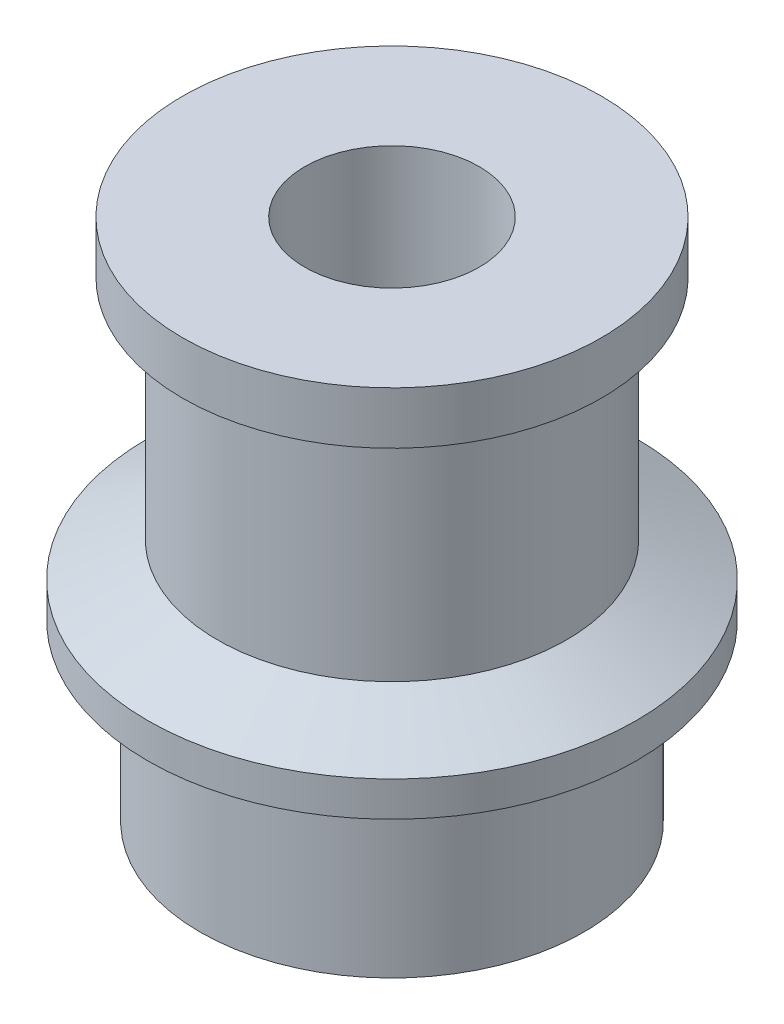
SolidWorks part; units mm, degrees
ref_plane "Front Plane" through (0, 0, 0) normal (0, 0, 1) x (1, 0, 0)
ref_plane "Top Plane" through (0, 0, 0) normal (0, 1, 0) x (1, 0, 0)
ref_plane "Right Plane" through (0, 0, 0) normal (1, 0, 0) x (0, 0, -1)
sketch "Sketch2" plane through (0, 0, 0) normal (0, 0, 1) x (1, 0, 0)
  line L0 (0, 0) -> (0, 27516.0501) construction
  line L1 (0, 14) -> (-5, 14)
  line L2 (-5, 14) -> (-5, 30)
  line L3 (-5, 30) -> (-12, 30)
  line L4 (-12, 30) -> (-12, 27)
  line L5 (-12, 27) -> (-10, 27)
  line L6 (-10, 27) -> (-10, 14)
  line L8 (-14, 12) -> (-14, 10)
  line L9 (-14, 10) -> (-11, 10)
  line L10 (-11, 10) -> (-11, 0)
  line L11 (-11, 0) -> (0, 0)
  line L12 (0, 0) -> (0, 14)
  line L13 (-10, 14) -> (-14, 12)
  dimension "D1" = 22
  dimension "D2" = 10
  dimension "D3" = 14
  dimension "D4" = 20
  dimension "D5" = 10
  dimension "D6" = 24
  dimension "D7" = 20
  dimension "D8" = 3
  dimension "D9" = 28
  dimension "D10" = 2
  dimension "D11" = 2
revolve "Revolve1" add sketch "Sketch2" angle 360 about L0
